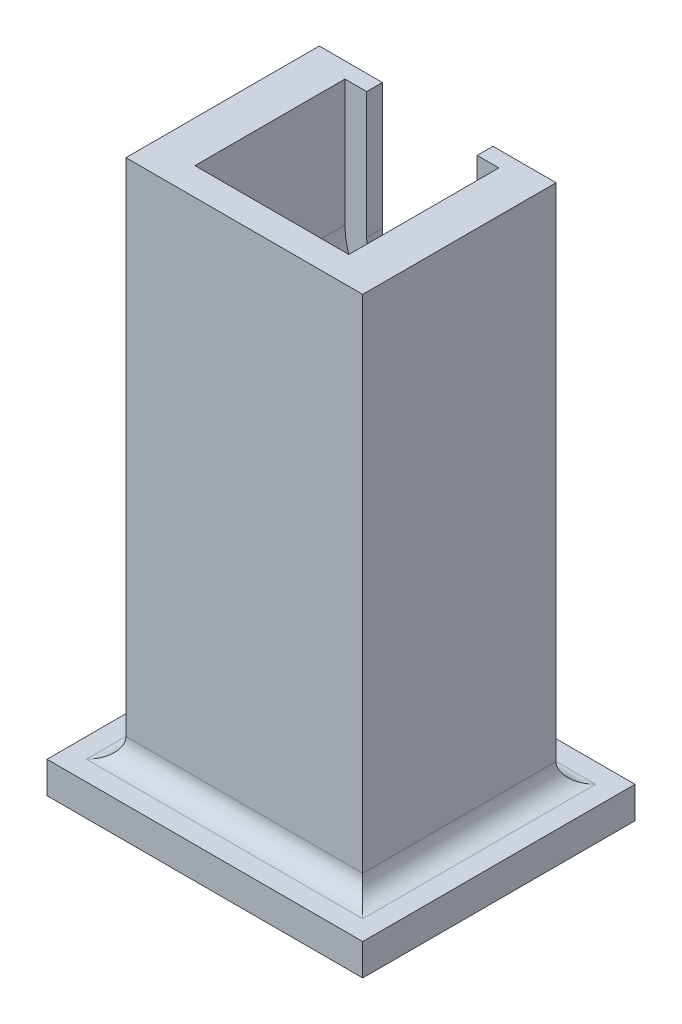
SolidWorks part; units mm, degrees
ref_plane "Front Plane" through (0, 0, 0) normal (0, 0, 1) x (1, 0, 0)
ref_plane "Top Plane" through (0, 0, 0) normal (0, 1, 0) x (1, 0, 0)
ref_plane "Right Plane" through (0, 0, 0) normal (1, 0, 0) x (0, 0, -1)
sketch "Sketch2" plane through (0, 0, 0) normal (0, 0, 1) x (1, 0, 0)
  line L0 (10.5, 108) -> (10.5, 140)
  line L1 (0, 0) -> (60, 0)
  line L2 (0, 0) -> (0, 140)
  line L3 (0, 140) -> (10.5, 140)
  line L4 (60, 0) -> (60, 140)
  line L5 (49.5, 108) -> (49.5, 140)
  line L6 (49.5, 140) -> (60, 140)
  arc A0 (10.5, 108) -> (49.5, 108) centre (30, 108) ccw
  dimension "D3" = 39
  dimension "D4" = 108
  dimension "D1" = 140
  dimension "D2" = 60
extrude "Boss-Extrude1" add sketch "Sketch2" along normal blind 38
sketch "Sketch3" plane through (0, 0, 38) normal (0, 0, 1) x (1, 0, 0)
  line L1 (0, 140) -> (60, 140)
  line L2 (0, 140) -> (0, 0)
  line L3 (0, 0) -> (60, 0)
  line L4 (60, 140) -> (60, 0)
extrude "Boss-Extrude2" add sketch "Sketch3" along normal blind 7
sketch "Sketch4" plane through (0, 0, 0) normal (0, 0, -1) x (-1, 0, 0)
  line L0 (-44, 108) -> (-44, 140)
  line L1 (-60, 140) -> (-44, 140)
  line L2 (-60, 140) -> (-60, 0)
  line L3 (-60, 0) -> (0, 0)
  line L4 (0, 140) -> (0, 0)
  line L5 (-16, 108) -> (-16, 140)
  line L6 (-16, 140) -> (0, 140)
  arc A0 (-44, 108) -> (-16, 108) centre (-30, 108) ccw
  dimension "D1" = 28
  dimension "D2" = 108
extrude "Boss-Extrude3" add sketch "Sketch4" along normal blind 4
sketch "Sketch5" plane through (0, 0, 0) normal (0, -1, 0) x (1, 0, 0)
  line L0 (0, 45) -> (0, -4) construction
  line L1 (-10, 55) -> (70, 55)
  line L2 (-10, 55) -> (-10, -14)
  line L3 (-10, -14) -> (70, -14)
  line L4 (70, 55) -> (70, -14)
  line L5 (60, 45) -> (60, -4) construction
  line L6 (0, 45) -> (60, 45) construction
  line L7 (60, -4) -> (0, -4) construction
  dimension "D1" = 10
  dimension "D2" = 10
  dimension "D3" = 10
  dimension "D4" = 10
extrude "Boss-Extrude4" add sketch "Sketch5" against normal blind 8
fillet "Fillet1" radius 5 4 edges at (60, 8, 20.5) (30, 8, -4) (0, 8, 20.5) (30, 8, 45)
